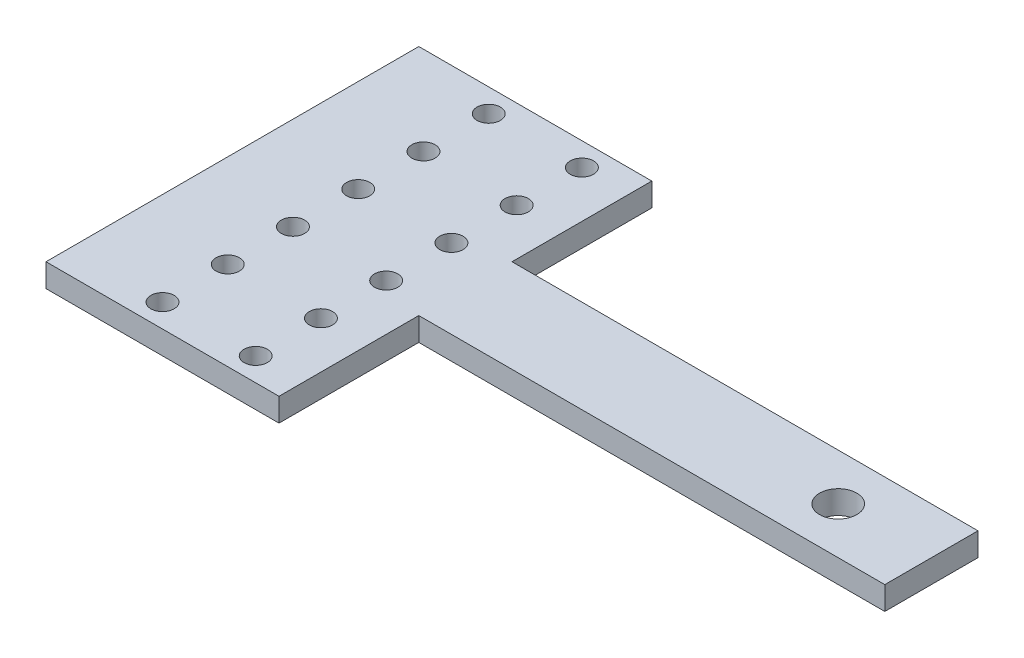
SolidWorks part; units mm, degrees
ref_plane "前视基准面" through (0, 0, 0) normal (0, 0, 1) x (1, 0, 0)
ref_plane "上视基准面" through (0, 0, 0) normal (0, 1, 0) x (1, 0, 0)
ref_plane "右视基准面" through (0, 0, 0) normal (1, 0, 0) x (0, 0, -1)
sketch "草图1" plane through (0, 0, 0) normal (0, 1, 0) x (1, 0, 0)
  line L0 (0, -20) -> (0, 20)
  line L1 (0, 20) -> (25, 20)
  line L2 (25, 20) -> (25, 5)
  line L3 (25, 5) -> (75, 5)
  line L4 (75, 5) -> (75, -5)
  line L5 (75, -5) -> (25, -5)
  line L6 (25, -5) -> (25, -20)
  line L7 (25, -20) -> (0, -20)
  point P4 (0, 0)
  dimension "D1" = 25
  dimension "D2" = 50
  dimension "D3" = 40
  dimension "D4" = 10
  dimension "D5" = 25
  dimension "D6" = 15
extrude "凸台-拉伸1" add sketch "草图1" along normal blind 2.5
sketch "草图2" plane through (0, 0, 0) normal (0, 1, 0) x (1, 0, 0)
  line L0 (25, 20) -> (0, 20) construction
  line L1 (0, 20) -> (0, -20) construction
  circle A0 centre (10, 17.5) radius 1.25
  circle A1 centre (20, 17.5) radius 1.25
  circle A2 centre (20, 10.5) radius 1.25
  circle A3 centre (20, 3.5) radius 1.25
  circle A4 centre (20, -3.5) radius 1.25
  circle A5 centre (20, -10.5) radius 1.25
  circle A6 centre (20, -17.5) radius 1.25
  circle A7 centre (10, 10.5) radius 1.25
  circle A8 centre (10, 3.5) radius 1.25
  circle A9 centre (10, -3.5) radius 1.25
  circle A10 centre (10, -10.5) radius 1.25
  circle A11 centre (10, -17.5) radius 1.25
  dimension "D3" = 2.5
  dimension "D4" = 2.5
  dimension "D5" = 10
  dimension "D1" = 2
  dimension "D2" = 6
extrude "切除-拉伸1" cut sketch "草图2" along normal through all
sketch "草图3" plane through (0, 0, 0) normal (0, 1, 0) x (1, 0, 0)
  line L0 (75, -5) -> (75, 5) construction
  circle A0 centre (65, 0) radius 2
  dimension "D1" = 4
  dimension "D2" = 10
extrude "切除-拉伸2" cut sketch "草图3" along normal blind 10
